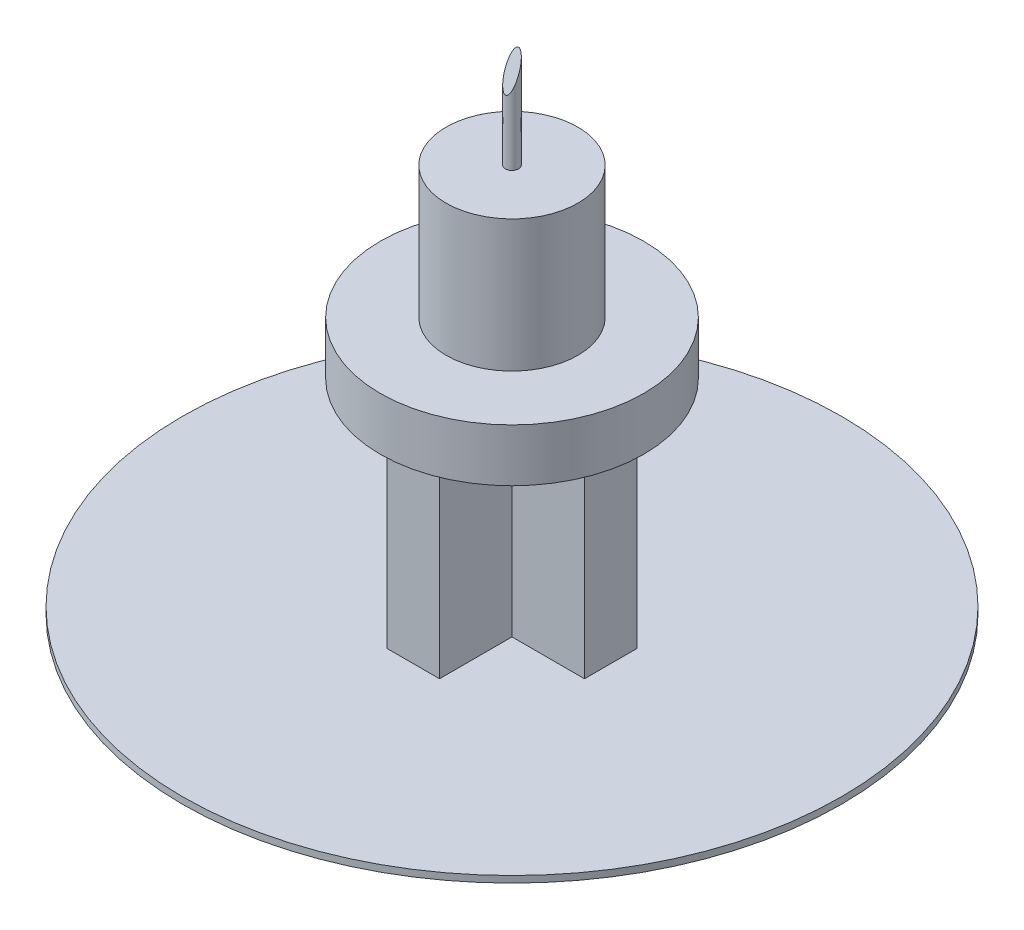
SolidWorks part; units mm, degrees
ref_plane "前视基准面" through (0, 0, 0) normal (0, 0, 1) x (1, 0, 0)
ref_plane "上视基准面" through (0, 0, 0) normal (0, 1, 0) x (1, 0, 0)
ref_plane "右视基准面" through (0, 0, 0) normal (1, 0, 0) x (0, 0, -1)
sketch "草图1" plane through (0, 0, 0) normal (0, 1, 0) x (1, 0, 0)
  circle A0 centre (0, 0) radius 10
  dimension "D1" = 20
extrude "凸台-拉伸1" add sketch "草图1" along normal blind 0.2
sketch "草图2" plane through (0, 0.2, 0) normal (0, 1, 0) x (1, 0, 0)
  line L0 (-3, 0) -> (0, 0) construction
  line L1 (-0.8, 3) -> (0.8, 3)
  line L2 (-0.8, 3) -> (-0.8, 0.8)
  line L3 (-0.8, -3) -> (0.8, -3)
  line L4 (0.8, 3) -> (0.8, 0.8)
  line L5 (-3, 0.8) -> (-0.8, 0.8)
  line L6 (-3, 0.8) -> (-3, -0.8)
  line L7 (-3, -0.8) -> (-0.8, -0.8)
  line L8 (3, 0.8) -> (3, -0.8)
  line L9 (0, 0) -> (0, 3) construction
  line L10 (0.8, 0) -> (0, 0) construction
  line L11 (0, -0.8) -> (0, 0) construction
  line L12 (-0.8, -0.8) -> (-0.8, -3)
  line L13 (0.8, 0.8) -> (3, 0.8)
  line L14 (0.8, -0.8) -> (0.8, -3)
  line L15 (0.8, -0.8) -> (3, -0.8)
  dimension "D1" = 6
  dimension "D2" = 1.6
extrude "凸台-拉伸2" add sketch "草图2" along normal blind 6
sketch "草图3" plane through (0, 6.2, 0) normal (0, 1, 0) x (1, 0, 0)
  circle A0 centre (0, 0) radius 4
  dimension "D1" = 8
extrude "凸台-拉伸3" add sketch "草图3" along normal blind 1.6
sketch "草图4" plane through (0, 0, 0) normal (0, -1, 0) x (-1, 0, 0)
  circle A0 centre (0, 0) radius 7
  dimension "D1" = 14
extrude "凸台-拉伸4" add sketch "草图4" along normal blind 0.22
sketch "草图5" plane through (0, 7.8, 0) normal (0, 1, 0) x (1, 0, 0)
  circle A0 centre (0, 0) radius 2
extrude "凸台-拉伸5" add sketch "草图5" along normal blind 4
sketch "草图6" plane through (0, 11.8, 0) normal (0, 1, 0) x (1, 0, 0)
  circle A0 centre (0, 0) radius 0.2
  dimension "D1" = 0.4
extrude "凸台-拉伸6" add sketch "草图6" along normal blind 3
sketch "草图7" plane through (0, 0, 0) normal (1, 0, 0) x (0, 0, -1)
  line L0 (0.2, 14.8) -> (-0.2, 14.8)
  line L1 (-0.2, 14.8) -> (-0.2, 13.7406)
  line L2 (-0.2, 13.7406) -> (0.2, 14.8)
  point P4 (-0.2, 14.0176)
  point P6 (-0.2, 13.7406)
extrude "切除-拉伸1" cut sketch "草图7" against normal mid plane 3
